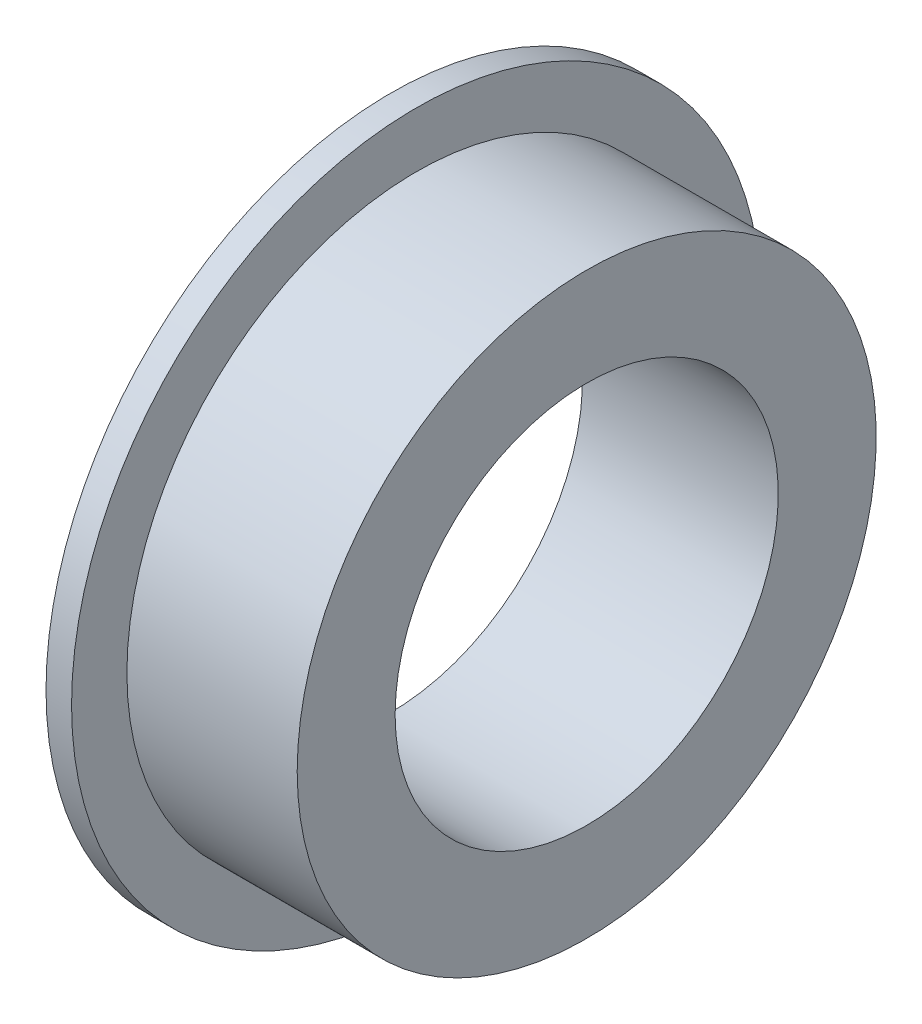
SolidWorks part; units mm, degrees
ref_plane "Front Plane" through (0, 0, 0) normal (0, 0, 1) x (1, 0, 0)
ref_plane "Top Plane" through (0, 0, 0) normal (0, 1, 0) x (1, 0, 0)
ref_plane "Right Plane" through (0, 0, 0) normal (1, 0, 0) x (0, 0, -1)
sketch "Sketch1" plane through (0, 0, 0) normal (0, 0, 1) x (1, 0, 0)
  line L0 (0, 0) -> (3.8641, 0) construction
  line L2 (0, 4.05) -> (0.3, 4.05)
  line L3 (0.3, 4.05) -> (0.3, 3.4)
  line L4 (0.3, 3.4) -> (2.3, 3.4)
  line L8 (0, 4.05) -> (0, 2.25)
  line L9 (2.3, 3.4) -> (2.3, 2.25)
  line L10 (2.3, 2.25) -> (0, 2.25)
  dimension "D1" = 0.3
  dimension "D2" = 4.05
  dimension "D3" = 1.8
  dimension "D4" = 2.3
  dimension "D5" = 0.65
revolve "Revolve1" add sketch "Sketch1" angle 360 about L0
